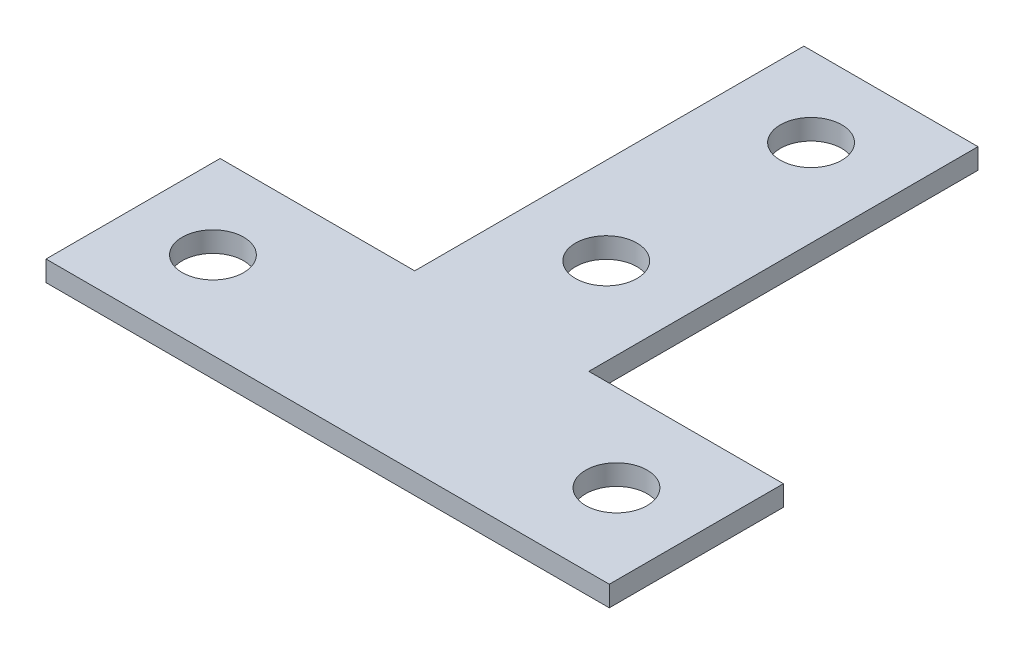
SolidWorks part; units mm, degrees
ref_plane "前视基准面" through (0, 0, 0) normal (0, 0, 1) x (1, 0, 0)
ref_plane "上视基准面" through (0, 0, 0) normal (0, 1, 0) x (1, 0, 0)
ref_plane "右视基准面" through (0, 0, 0) normal (1, 0, 0) x (0, 0, -1)
other "Configuration Table"
sketch "草图1" plane through (0, 0, 0) normal (0, 1, 0) x (1, 0, 0)
  line L1 (-27.5, 27.5) -> (27.5, 27.5)
  line L2 (-27.5, 27.5) -> (-27.5, -27.5)
  line L3 (-27.5, -27.5) -> (27.5, -27.5)
  line L4 (27.5, 27.5) -> (27.5, -27.5)
  line L5 (-27.5, 27.5) -> (27.5, -27.5) construction
  line L6 (-27.5, -27.5) -> (27.5, 27.5) construction
  point P0 (0, 0)
  dimension "D1" = 0
  dimension "D2" = 55
  dimension "D3" = 55
extrude "凸台-拉伸1" add sketch "草图1" along normal blind 2
sketch "草图2" plane through (0, 2, 0) normal (0, 1, 0) x (1, 0, 0)
  line L0 (-27.5, 27.5) -> (-27.5, -27.5) construction
  line L1 (-27.5, -10.5) -> (-8.5, -10.5)
  line L2 (-27.5, -10.5) -> (-27.5, 27.5)
  line L3 (-27.5, 27.5) -> (-8.5, 27.5)
  line L4 (-8.5, -10.5) -> (-8.5, 27.5)
  line L5 (27.5, 27.5) -> (-27.5, 27.5) construction
  line L6 (-27.5, -27.5) -> (27.5, -27.5) construction
  line L7 (0, -1000) -> (0, 49000) construction
  line L8 (27.5, 27.5) -> (8.5, 27.5)
  line L9 (8.5, -10.5) -> (8.5, 27.5)
  line L10 (27.5, -10.5) -> (8.5, -10.5)
  line L11 (27.5, -10.5) -> (27.5, 27.5)
  dimension "D1" = 17
  dimension "D2" = 8.5
extrude "切除-拉伸1" cut sketch "草图2" against normal through all
sketch "草图3" plane through (0, 2, 0) normal (0, 1, 0) x (1, 0, 0)
  line L0 (-27.5, -10.5) -> (-27.5, -27.5) construction
  line L1 (27.5, -27.5) -> (27.5, -10.5) construction
  line L2 (-27.5, -27.5) -> (27.5, -27.5) construction
  line L3 (8.5, 27.5) -> (-8.5, 27.5) construction
  circle A0 centre (-19.7, -19) radius 3
  circle A1 centre (19.7, -19) radius 3
  circle A2 centre (0, -0.3) radius 3
  circle A3 centre (0, 19.7) radius 3
  dimension "D1" = 6
  dimension "D2" = 6
  dimension "D3" = 6
  dimension "D4" = 6
  dimension "D5" = 7.8
  dimension "D6" = 7.8
  dimension "D7" = 8.5
  dimension "D8" = 8.5
  dimension "D9" = 7.8
  dimension "D10" = 20
extrude "切除-拉伸2" cut sketch "草图3" against normal through all
